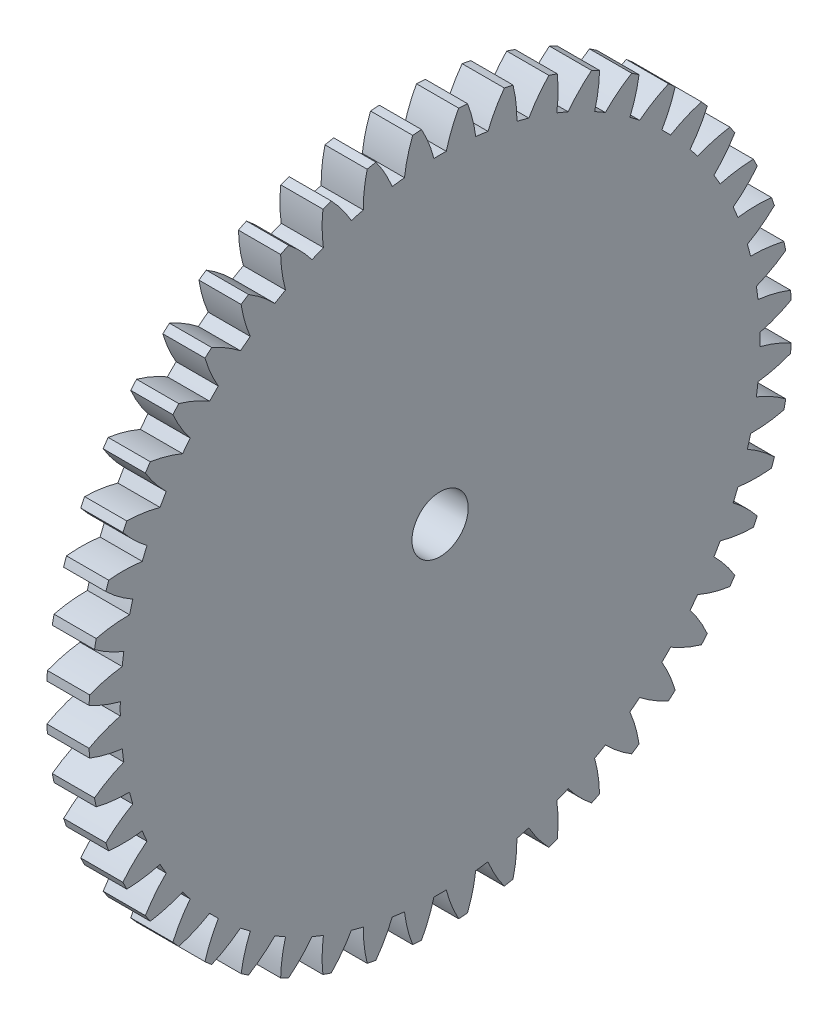
SolidWorks part; units mm, degrees
ref_plane "Plane1" through (0, 0, 0) normal (0, 0, 1) x (1, 0, 0)
ref_plane "Plane2" through (0, 0, 0) normal (0, 1, 0) x (1, 0, 0)
ref_plane "Plane3" through (0, 0, 0) normal (1, 0, 0) x (0, 0, -1)
sketch "HoldingSke" plane through (0, 0, 0) normal (0, 1, 0) x (1, 0, 0)
  line L0 (0, 0) -> (1.3383, -1.4863)
  line L1 (-15, 0) -> (100, 0) construction
  line L2 (0, 0) -> (-2.1039, 2.3779)
  line L3 (0, 0) -> (-11.863, 4.5341)
  line L4 (0, 0) -> (5.7786, 6.4178)
  line L5 (0, 0) -> (-46.8476, -17.4728)
  line L6 (0, 0) -> (-1.6579, -1.1186)
  line L7 (-2.1039, 2.3779) -> (8.6586, 51.2059)
  line L8 (-76.2, 54.61) -> (-75.9, 54.61)
  line L9 (-71.009, 38.7566) -> (-53.1078, 45.2721)
  line L10 (-76.2, 71.12) -> (104.1128, 71.12)
  line L11 (0, 0) -> (-2, 0)
  line L12 (-76.2, 101.6) -> (-76.181, 101.6)
  line L13 (24.9733, 27.94) -> (52.9518, 28.4284)
  line L14 (24.9733, 27.94) -> (24.9743, 27.94)
  line L15 (24.9733, 27.94) -> (100.4006, 29.5858)
  line L16 (-63.627, -0.5) -> (-12.827, -0.5)
  circle A0 centre (0, 0) radius 1
  circle A1 centre (0, 0) radius 11.374
  circle A2 centre (0, 0) radius 37.5
  circle A3 centre (0, 0) radius 1
  dimension "MHD" = 22.748
  dimension "Hub_dia" = 75
  dimension "Bore" = 2
  dimension "MBD" = 2
  dimension "Num_teeth" = 48
  dimension "Pitch" = 2
  dimension "Overall_len" = 50
  dimension "Show_teeth" = 48
  dimension "Thickness" = 2
  dimension "OAL" = 50.0001
  dimension "T_dim" = 0.3
  dimension "Ap" = 20
  dimension "H" = 19.05
  dimension "Pitch_radius" = 180.3128
  dimension "Width" = 2
  dimension "Backlash" = 0.019
  dimension "Addendum_fac" = 1
  dimension "Dedendum_fac" = 1.25
  dimension "Clearance_fac" = 0.25
  dimension "Dedendum_add" = 0.001
  dimension "Module" = 0.5
sketch "BasProSke" plane through (0, 0, 0) normal (0, 1, 0) x (1, 0, 0)
  line L0 (-10, 0) -> (60, 0) construction
  line L1 (0, 0) -> (0, 12.5)
  line L2 (0, 0) -> (1.5, 0)
  line L3 (1.5, 0) -> (1.5, 12.5)
  line L4 (1.5, 12.5) -> (0, 12.5)
  dimension "Thickness" = 1.5
  dimension "Diameter" = 25
revolve "Base-Revolve" add sketch "BasProSke" angle 360 about L0
sketch "TooCutSke" plane through (0, 0, 0) normal (1, 0, 0) x (0, 0, -1)
  line L1 (0, 0) -> (0, 107) construction
  line L2 (0, 0) -> (-0.4259, 11.9924) construction
  line L3 (0, 0) -> (-1.569, 23.9379) construction
  line L4 (-0.4259, 11.9924) -> (-0.7845, 11.9689) construction
  arc A0 (0.2196, 11.3719) -> (-0.2196, 11.3719) centre (0, 0) ccw
  arc A1 (0.6737, 12.5073) -> (-0.6737, 12.5073) centre (0, 0) ccw
  circle A2 centre (0, 0) radius 12 construction
  circle A3 centre (0, 0) radius 11.2763 construction
  arc A4 (-0.2196, 11.3719) -> (-0.6737, 12.5073) centre (-4.8672, 10.1718) ccw
  arc A5 (0.6737, 12.5073) -> (0.2196, 11.3719) centre (4.8672, 10.1718) ccw
  dimension "Root_dia" = 22.748
  dimension "Overcut_dia" = 25.0508
  dimension "Pitch_dia" = 24
  dimension "Base_dia" = 22.5526
  dimension "Flank_rad" = 4.8
  dimension "Half_ang" = 3.75
  dimension "Half_CT" = 0.3594
extrude "ToothCut" cut sketch "TooCutSke" along normal through all
fillet "Breaks" [suppressed] radius 0.01
fillet "RootFillets" [suppressed] radius 0.126
pattern_circular "TeethCuts" count 48 every 7.5 about axis through (-10, 0, 0) along (1, 0, 0) of "ToothCut", "RootFillets", "Breaks"
sketch "HubNeaOneSke" plane through (0, 0, 0) normal (-1, 0, 0) x (0, 0, 1)
  circle A0 centre (0, 0) radius 11.374
  dimension "Diameter" = 22.748
extrude "HubNearOne" [suppressed] add sketch "HubNeaOneSke" along normal blind 48.5001
sketch "HubNeaBotSke" plane through (0, 0, 0) normal (-1, 0, 0) x (0, 0, 1)
  circle A0 centre (0, 0) radius 11.374
  dimension "Diameter" = 22.748
extrude "HubNearBoth" [suppressed] add sketch "HubNeaBotSke" along normal blind 24.25
ref_plane "FarPln" through (1.5, 0, 0) normal (1, 0, 0) x (0, 0, -1)
sketch "HubFarSke" plane through (1.5, 0, 0) normal (1, 0, 0) x (0, 0, -1)
  circle A0 centre (0, 0) radius 11.374
  dimension "Diameter" = 22.748
extrude "HubFar" [suppressed] add sketch "HubFarSke" along normal blind 24.25
sketch "BorSke" plane through (0, 0, 0) normal (1, 0, 0) x (0, 0, -1)
  circle A0 centre (0, 0) radius 1
  dimension "Diameter" = 2
extrude "Bore" cut sketch "BorSke" along normal mid plane 100.0001
sketch "KeySke" plane through (0, 0, 0) normal (1, 0, 0) x (0, 0, -1)
  line L0 (-0.4, 0) -> (-0.4, 1.3)
  line L1 (-0.4, 1.3) -> (0.4, 1.3)
  line L2 (0.4, 1.3) -> (0.4, 0)
  line L3 (0, 0) -> (0, 34) construction
  line L4 (-0.4, 0) -> (0.4, 0)
  dimension "Offset" = 1.3
  dimension "Width" = 0.8
extrude "Keyway" [suppressed] cut sketch "KeySke" along normal mid plane 100.0001
pattern_circular "Keyway2" [suppressed] count 2 every 90 about axis through (-10, 0, 0) along (1, 0, 0)
sketch "Sketch2" plane through (0, 0, 0) normal (-1, 0, 0) x (0, 0, 1)
  circle A0 centre (0, 0) radius 1
  circle A1 centre (0, 0) radius 2.25
  dimension "D1" = 4.5
extrude "Boss-Extrude2" add sketch "Sketch2" along normal blind 0.5
equation "' \"Module@HoldingSke\" = 6.35"
equation "' \"Num_teeth@HoldingSke\" = 12"
equation "' \"Ap@HoldingSke\" =  20"
equation "' \"Ap@HoldingSke\" = 20"
equation "' \"Width@HoldingSke\" = 0.5 * 25.4"
equation "' \"Hub_dia@HoldingSke\"= 1 * 25.4"
equation "' \"Hub_dia@HoldingSke\" = 1 * 25.4"
equation "' \"Overall_len@HoldingSke\" = 1.0 * 25.4"
equation "' \"Bore@HoldingSke\" = 0.75 * 25.4"
equation "' \"T_dim@HoldingSke\" = 0.1 * 25.4"
equation "' \"Width@KeySke\" = 0.25 * 25.4"
equation "' \"Show_teeth@HoldingSke\" = 13"
equation "' \"Backlash@HoldingSke\" = 0.009 * 25.4"
equation "' \"Addendum_fac@HoldingSke\" = 1.0"
equation "' \"Dedendum_fac@HoldingSke\" = 1.25"
equation "' \"Dedendum_add@HoldingSke\" = 0.00005 * 25.4"
equation "' \"Clearance_fac@HoldingSke\" = 0.25"
equation "\"Pitch@HoldingSke\" = 1 / \"Module@HoldingSke\""
equation "\"Overcut_dia@TooCutSke\" = (\"Num_teeth@HoldingSke\" + 2 * \"Addendum_fac@HoldingSke\") / \"Pitch@HoldingSke\" + 0.002 * 25.4"
equation "\"Pitch_dia@TooCutSke\" = \"Num_teeth@HoldingSke\" / \"Pitch@HoldingSke\""
equation "\"Base_dia@TooCutSke\" = \"Num_teeth@HoldingSke\" / \"Pitch@HoldingSke\" * cos((\"Ap@HoldingSke\"  * 3.14159265 / 180))"
equation "\"Root_dia@TooCutSke\" = (\"Num_teeth@HoldingSke\" + 2) / \"Pitch@HoldingSke\" - 2 * (\"Addendum_fac@HoldingSke\" + \"Dedendum_fac@HoldingSke\") / \"Pitch@HoldingSke\" - \"Dedendum_add@HoldingSke\" * 2"
equation "\"Half_ang@TooCutSke\" = 180 / \"Num_teeth@HoldingSke\""
equation "\"Half_CT@TooCutSke\" = \"Num_teeth@HoldingSke\" / \"Pitch@HoldingSke\" * sin((3.14159265 / 2 / \"Num_teeth@HoldingSke\")) / 2 - 7 * \"Backlash@HoldingSke\" / 4"
equation "\"Flank_rad@TooCutSke\" = \"Num_teeth@HoldingSke\" / \"Pitch@HoldingSke\" / 5"
equation "\"Radius@RootFillets\" = \"Clearance_fac@HoldingSke\" / \"Pitch@HoldingSke\" + \"Dedendum_add@HoldingSke\""
equation "\"Break_rad@Breaks\" = 0.02 / \"Pitch@HoldingSke\""
equation "\"Thickness@HoldingSke\" = \"Width@HoldingSke\""
equation "\"OAL@HoldingSke\" = \"Thickness@HoldingSke\""
equation "\"MHD@HoldingSke\" = (\"Num_teeth@HoldingSke\" + 2) / \"Pitch@HoldingSke\" - 2 * (\"Addendum_fac@HoldingSke\" + \"Dedendum_fac@HoldingSke\")  / \"Pitch@HoldingSke\" - \"Dedendum_add@HoldingSke\" * 2"
equation "\"MBD@HoldingSke\" = (\"Num_teeth@HoldingSke\" + 2) / \"Pitch@HoldingSke\" - 2 * (\"Addendum_fac@HoldingSke\" + \"Dedendum_fac@HoldingSke\")  / \"Pitch@HoldingSke\" - \"Dedendum_add@HoldingSke\" * 2 - 0.002 * 25.4"
equation "\"MHD@HoldingSke\" = ((sgn( \"MHD@HoldingSke\" - \"Hub_dia@HoldingSke\" )-1)*( \"MHD@HoldingSke\" - \"Hub_dia@HoldingSke\" ))/-2+ \"Hub_dia@HoldingSke\""
equation "\"MBD@HoldingSke\" = ((sgn( \"MBD@HoldingSke\" - \"Bore@HoldingSke\" )-1)*( \"MBD@HoldingSke\" - \"Bore@HoldingSke\" ))/-2+ \"Bore@HoldingSke\""
equation "\"OAL@HoldingSke\" = ((sgn( \"OAL@HoldingSke\" - \"Overall_len@HoldingSke\" )+1)*( \"OAL@HoldingSke\" - \"Overall_len@HoldingSke\" ))/2 + \"Overall_len@HoldingSke\" + 0.000002 * 25.4"
equation "\"Num_teeth@TeethCuts\" = int( \"Show_teeth@HoldingSke\" ) + 1"
equation "\"Num_teeth@TeethCuts\" = ((sgn( \"Num_teeth@TeethCuts\" - \"Num_teeth@HoldingSke\" )-1)*( \"Num_teeth@TeethCuts\" - \"Num_teeth@HoldingSke\" ))/-2+ \"Num_teeth@HoldingSke\""
equation "\"Num_teeth@TeethCuts\" = ((sgn( \"Num_teeth@TeethCuts\" - 2.0)+1)*( \"Num_teeth@TeethCuts\" - 2.0))/2 +2.0"
equation "\"Angle@TeethCuts\" = 360.0 / \"Num_teeth@HoldingSke\""
equation "\"Diameter@BasProSke\" = (\"Num_teeth@HoldingSke\" + 2 * \"Addendum_fac@HoldingSke\") / \"Pitch@HoldingSke\""
equation "\"Thickness@BasProSke\"=\"Thickness@HoldingSke\"-0.5"
equation "' \"Fillet_rad@BasProSke\" =  \"Thickness@HoldingSke\" * 0.05"
equation "' \"Fillet_rad@BasProSke\" = \"Thickness@HoldingSke\" * 0.05"
equation "\"MHD@HoldingSke\" = ((sgn( \"MHD@HoldingSke\" - \"Root_dia@TooCutSke\" )-1)*( \"MHD@HoldingSke\" - \"Root_dia@TooCutSke\" ))/-2+ \"Root_dia@TooCutSke\""
equation "\"Diameter@HubNeaOneSke\" = \"MHD@HoldingSke\""
equation "\"Length@HubNearOne\" = \"OAL@HoldingSke\" - \"Thickness@BasProSke\""
equation "\"Diameter@HubNeaBotSke\" = \"MHD@HoldingSke\""
equation "\"Length@HubNearBoth\" = ( \"OAL@HoldingSke\" - \"Thickness@BasProSke\" ) / 2.0"
equation "\"Thickness@FarPln\" = \"Thickness@BasProSke\""
equation "\"Diameter@HubFarSke\" = \"MHD@HoldingSke\""
equation "\"Length@HubFar\" = ( \"OAL@HoldingSke\" - \"Thickness@BasProSke\" ) / 2.0"
equation "\"Diameter@BorSke\" = \"MBD@HoldingSke\""
equation "\"D1@Bore\" = \"OAL@HoldingSke\" * 2.0"
equation "\"D1@Keyway\" = \"OAL@HoldingSke\" * 2.0"
equation "\"Offset@KeySke\" = \"T_dim@HoldingSke\" + \"MBD@HoldingSke\" / 2.0"
